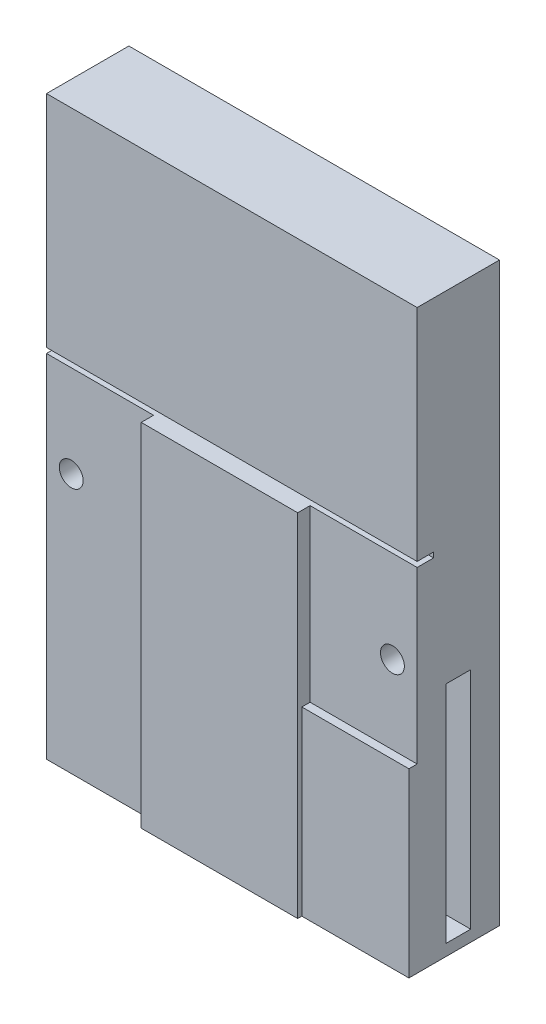
SolidWorks part; units mm, degrees
ref_plane "Front Plane" through (0, 0, 0) normal (0, 0, 1) x (1, 0, 0)
ref_plane "Top Plane" through (0, 0, 0) normal (0, 1, 0) x (1, 0, 0)
ref_plane "Right Plane" through (0, 0, 0) normal (1, 0, 0) x (0, 0, -1)
sketch "Sketch2" plane through (0, 0, 0) normal (0, 1, 0) x (1, 0, 0)
  line L1 (22.5, 5) -> (-22.5, 5)
  line L2 (22.5, 5) -> (22.5, -5)
  line L3 (22.5, -5) -> (-22.5, -5)
  line L4 (-22.5, 5) -> (-22.5, -5)
  line L5 (22.5, 5) -> (-22.5, -5) construction
  line L6 (22.5, -5) -> (-22.5, 5) construction
  point P0 (0, 0)
  dimension "D1" = 10
  dimension "D2" = 45
extrude "Boss-Extrude1" add sketch "Sketch2" along normal blind 40
sketch "Sketch3" plane through (0, 0, -5) normal (0, 0, -1) x (-1, 0, 0)
  line L0 (0, 0) -> (0, 40) construction
  line L1 (-22.5, 40) -> (22.5, 40) construction
  line L3 (22.5, 40) -> (22.5, 0) construction
  line L4 (-22.5, 40) -> (-22.5, 0) construction
  line L5 (-22.5, 0) -> (22.5, 0) construction
  line L6 (-22.5, 11.5) -> (22.5, 11.5) construction
  circle A0 centre (19.5, 2.25) radius 1.45
  circle A3 centre (-19.5, 2.25) radius 1.45
  circle A4 centre (-19.5, 20.75) radius 1.45
  circle A5 centre (19.5, 20.75) radius 1.45
  dimension "D3" = 2.9
  dimension "D4" = 3
  dimension "D1" = 3
  dimension "D2" = 2.25
sketch "Sketch4" plane through (0, 40, 0) normal (0, 1, 0) x (1, 0, 0)
  line L1 (-22.5, 5) -> (22.5, 5)
  line L2 (-22.5, 5) -> (-22.5, -5)
  line L3 (-22.5, -5) -> (22.5, -5)
  line L4 (22.5, 5) -> (22.5, -5)
extrude "Boss-Extrude2" add sketch "Sketch4" along normal blind 10
sketch "Sketch6" plane through (0, 0, -5) normal (0, 0, -1) x (-1, 0, 0)
  line L2 (-22.5, 23) -> (22.7712, 23) construction
  circle A1 centre (-19.5, 20.75) radius 1.45 construction
  dimension "D1" = 2.25
sketch "Sketch8" plane through (0, 0, 0) normal (0, -1, 0) x (1, 0, 0)
  line L1 (-22.5, 5) -> (22.5, 5)
  line L2 (-22.5, 5) -> (-22.5, -5)
  line L3 (-22.5, -5) -> (22.5, -5)
  line L4 (22.5, 5) -> (22.5, -5)
extrude "Boss-Extrude3" add sketch "Sketch8" along normal blind 20
sketch "Sketch9" plane through (0, 0, 5) normal (0, 0, 1) x (1, 0, 0)
  line L0 (22.5, 11.5) -> (-22.5, 11.5) construction
  line L1 (-22.5, 50) -> (-22.5, -20) construction
  line L2 (22.5, 50) -> (22.5, -20) construction
  circle A0 centre (19.5, 20.75) radius 1.45 construction
  circle A1 centre (19.5, 2.25) radius 1.45 construction
  circle A2 centre (19.5, 11.5) radius 1.45
  circle A3 centre (-19.5, 11.5) radius 1.45
  dimension "D1" = 18.5
  dimension "D2" = 3
  dimension "D3" = 3
  dimension "D4" = 3
extrude "Cut-Extrude2" cut sketch "Sketch9" against normal blind 20
sketch "Sketch10" plane through (0, 0, 5) normal (0, 0, 1) x (1, 0, 0)
  line L1 (-22.5, 50) -> (-22.5, -20) construction
  line L2 (-22.5, 23.2975) -> (22.5, 23.2975)
  line L3 (-22.5, 23.2975) -> (-22.5, 22.6713)
  line L4 (-22.5, 22.6713) -> (22.5, 22.6713)
  line L5 (22.5, 23.2975) -> (22.5, 22.6713)
  line L6 (22.5, 50) -> (22.5, -20) construction
extrude "Cut-Extrude3" cut sketch "Sketch10" against normal blind 2
sketch "Sketch11" plane through (0, 0, 5) normal (0, 0, 1) x (1, 0, 0)
  line L0 (-22.5, 22.6713) -> (22.5, 22.6713) construction
  line L1 (-9.5, 22.6713) -> (9.5, 22.6713)
  line L2 (-9.5, 22.6713) -> (-9.5, -20)
  line L3 (-9.5, -20) -> (9.5, -20)
  line L4 (9.5, 22.6713) -> (9.5, -20)
  line L5 (22.5, -20) -> (-22.5, -20) construction
  line L6 (22.5, 22.6713) -> (22.5, -20) construction
  line L8 (-22.5, 22.6713) -> (-22.5, -20) construction
  dimension "D1" = 19
  dimension "D2" = 13
  dimension "D3" = 13
extrude "Boss-Extrude4" add sketch "Sketch11" along normal blind 1.5
sketch "Sketch12" plane through (22.5, 0, 0) normal (1, 0, 0) x (0, 0, -1)
  line L0 (0, 8.6713) -> (0, -20) construction
  line L1 (5, -20) -> (-5, -20) construction
  line L2 (-3, 22.6713) -> (-5, 22.6713) construction
  line L3 (-1.5, 8.6713) -> (1.5, 8.6713)
  line L4 (-1.5, 8.6713) -> (-1.5, -18.615)
  line L5 (-1.5, -18.615) -> (1.5, -18.615)
  line L6 (1.5, 8.6713) -> (1.5, -18.615)
  dimension "D1" = 3
  dimension "D2" = 1.385
  dimension "D3" = 14
extrude "Cut-Extrude6" cut sketch "Sketch12" against normal blind 10
sketch "Sketch13" plane through (0, 0, 5) normal (0, 0, 1) x (1, 0, 0)
  line L0 (9.5, -20) -> (9.5, 22.6713) construction
  line L1 (9.5, 2) -> (22.5, 2)
  line L2 (9.5, 2) -> (9.5, -20)
  line L3 (9.5, -20) -> (22.5, -20)
  line L4 (22.5, 2) -> (22.5, -20)
  dimension "D1" = 22
extrude "Boss-Extrude5" add sketch "Sketch13" along normal blind 1
